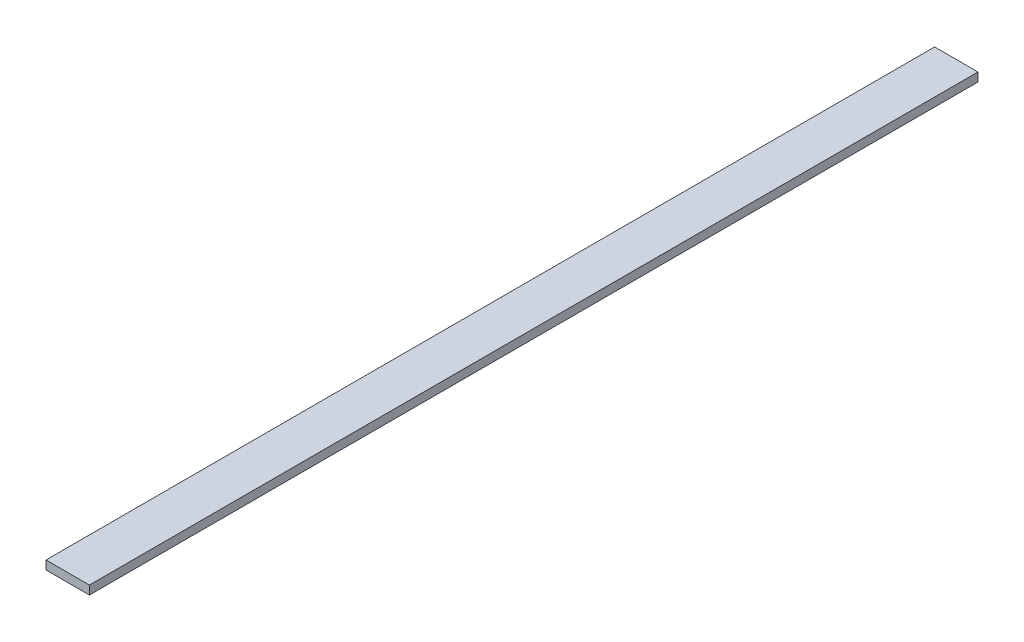
SolidWorks part; units mm, degrees
ref_plane "Front Plane" through (0, 0, 0) normal (0, 0, 1) x (1, 0, 0)
ref_plane "Top Plane" through (0, 0, 0) normal (0, 1, 0) x (1, 0, 0)
ref_plane "Right Plane" through (0, 0, 0) normal (1, 0, 0) x (0, 0, -1)
sketch "Sketch1" plane through (0, 0, 0) normal (0, 1, 0) x (1, 0, 0)
  line L1 (-10, 204.7875) -> (10, 204.7875)
  line L2 (-10, 204.7875) -> (-10, -204.7875)
  line L3 (-10, -204.7875) -> (10, -204.7875)
  line L4 (10, 204.7875) -> (10, -204.7875)
  line L5 (-10, 204.7875) -> (10, -204.7875) construction
  line L6 (-10, -204.7875) -> (10, 204.7875) construction
  point P0 (0, 0)
extrude "Boss-Extrude1" add sketch "Sketch1" along normal blind 4
